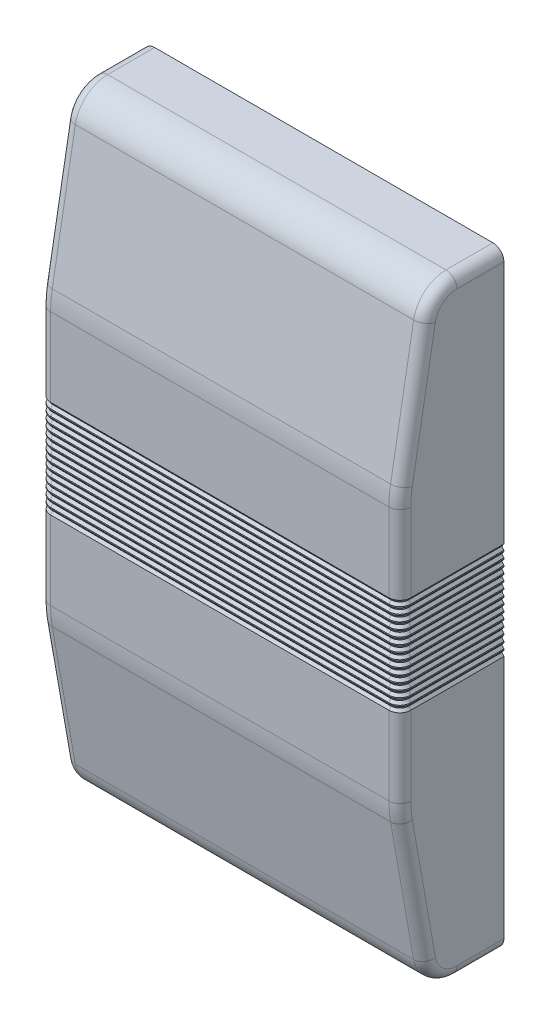
SolidWorks part; units mm, degrees
material "ABS"
ref_plane "Front Plane" through (0, 0, 0) normal (0, 0, 1) x (1, 0, 0)
ref_plane "Top Plane" through (0, 0, 0) normal (0, 1, 0) x (1, 0, 0)
ref_plane "Right Plane" through (0, 0, 0) normal (1, 0, 0) x (0, 0, -1)
sketch "Reference" plane through (0, 0, 0) normal (0, 0, 1) x (1, 0, 0)
  line L1 (0, 0) -> (65.8, 0) construction
  line L2 (0, 0) -> (0, 111.1) construction
  line L3 (0, 111.1) -> (65.8, 111.1) construction
  line L4 (65.8, 0) -> (65.8, 111.1) construction
  dimension "D1" = 65.8
  dimension "D2" = 111.1
sketch "Sketch2" plane through (0, 0, 0) normal (1, 0, 0) x (0, 0, -1)
  line L0 (0, 111.1) -> (-13.6132, 111.1)
  line L1 (0, 0) -> (0, 111.1) construction
  line L2 (0, 0) -> (0, 111.1) construction
  line L3 (-13.6132, 111.1) -> (-19, 80.55)
  line L4 (-19, 80.55) -> (-19, 30.55)
  line L5 (-19, 30.55) -> (-13.6132, 0)
  line L6 (-13.6132, 0) -> (0, 0)
  line L7 (0, 111.1) -> (0, 0)
  point P13 (0, 55.55)
  point P16 (-19, 55.55)
  point P32 (-19, 80.55)
  dimension "D3" = 50
  dimension "D4" = 19
  dimension "D8" = 170
extrude "Extrude side profile" add sketch "Sketch2" along normal up to vertex (65.8 mm away) up to point (65.8, 111.1, 0)
fillet "Cosmetic fillet" radius 20 2 edges at (32.9, 80.55, 19) (32.9, 30.55, 19)
fillet "Cosmetic fillet 2" radius 6 2 edges at (32.9, 0, 13.6132) (32.9, 111.1, 13.6132)
fillet "Cosmetic fillet 3" radius 2 18 edges at (0, 0, 4.2893) (0, 1.4037, 12.4353) (0, 16.8925, 16.5918) (0, 30.5567, 18.9239) (0, 55.55, 19) (0, 80.5433, 18.9239) (0, 94.2075, 16.5918) (0, 109.6963, 12.4353) (65.8, 0, 4.2893) (65.8, 1.4037, 12.4353) (65.8, 16.8925, 16.5918) (65.8, 30.5567, 18.9239) (65.8, 55.55, 19) (65.8, 80.5433, 18.9239) (65.8, 94.2075, 16.5918) (65.8, 109.6963, 12.4353) (0, 111.1, 4.2893) (65.8, 111.1, 4.2893)
shell "Shell1" thickness 3.2
fillet "Fillet internals" radius 1.5 18 edges at (3.2, 107.9, 4.2893) (3.2, 107.2449, 10.3784) (3.2, 93.6519, 13.4404) (3.2, 80.2644, 15.7361) (3.2, 55.55, 15.8) (3.2, 30.8356, 15.7361) (3.2, 17.4481, 13.4404) (3.2, 3.8551, 10.3784) (62.6, 3.2, 4.2893) (62.6, 3.8551, 10.3784) (62.6, 17.4481, 13.4404) (62.6, 30.8356, 15.7361) (62.6, 55.55, 15.8) (62.6, 80.2644, 15.7361) (62.6, 93.6519, 13.4404) (62.6, 107.2449, 10.3784) (3.2, 3.2, 4.2893) (62.6, 107.9, 4.2893)
sketch "Sketch3" plane through (0, 0, 0) normal (0, 0, -1) x (-1, 0, 0)
  line L37 (-63.8, 111.1) -> (-2, 111.1) construction
  line L38 (0, 2) -> (0, 109.1) construction
  line L39 (-63.8, 0) -> (-2, 0) construction
  line L40 (-65.8, 2) -> (-65.8, 109.1) construction
  line L45 (-1.6, 4.7) -> (-1.6, 106.4)
  line L46 (-61.1, 1.6) -> (-4.7, 1.6)
  line L47 (-64.2, 106.4) -> (-64.2, 4.7)
  line L48 (-4.7, 109.5) -> (-61.1, 109.5)
  line L49 (-61.1, 3.2) -> (-4.7, 3.2)
  line L50 (-62.6, 106.4) -> (-62.6, 4.7)
  line L51 (-4.7, 107.9) -> (-61.1, 107.9)
  line L52 (-3.2, 4.7) -> (-3.2, 106.4)
  line L53 (-61.1, 3.2) -> (-4.7, 3.2)
  line L54 (-62.6, 106.4) -> (-62.6, 4.7)
  line L55 (-4.7, 107.9) -> (-61.1, 107.9)
  line L56 (-3.2, 4.7) -> (-3.2, 106.4)
  line L57 (-61.1, 3.2) -> (-61.1, 1.6)
  line L58 (-62.6, 4.7) -> (-64.2, 4.7)
  line L59 (-4.7, 3.2) -> (-4.7, 1.6)
  line L60 (-3.2, 4.7) -> (-1.6, 4.7)
  line L61 (-3.2, 106.4) -> (-1.6, 106.4)
  line L62 (-4.7, 107.9) -> (-4.7, 109.5)
  line L63 (-61.1, 107.9) -> (-61.1, 109.5)
  line L64 (-62.6, 106.4) -> (-64.2, 106.4)
  arc A36 (-62.6, 4.7) -> (-61.1, 3.2) centre (-61.1, 4.7) ccw
  arc A37 (-61.1, 107.9) -> (-62.6, 106.4) centre (-61.1, 106.4) ccw
  arc A38 (-3.2, 106.4) -> (-4.7, 107.9) centre (-4.7, 106.4) ccw
  arc A39 (-4.7, 3.2) -> (-3.2, 4.7) centre (-4.7, 4.7) ccw
  dimension "D1" = 1.6
  dimension "D2" = 0
  dimension "D3" = 1.6
  dimension "D4" = 1.6
  dimension "D5" = 1.6
extrude "Extrude mating boss" add sketch "Sketch3" along normal blind 1.5
other "Tolerance mating boss" face at (32.9, 109.5, -0.75) face at (1.6, 55.55, -0.75) face at (32.9, 1.6, -0.75) face at (64.2, 55.55, -0.75) parameters "D1"=0.2
ref_plane "Mid plane" through (0, 55.55, 0) normal (0, 1, 0) x (1, 0, 0)
sketch "Intersection curve" plane through (0, 55.55, 0) normal (0, 1, 0) x (1, 0, 0)
  line L0 (63.8, -19) -> (2, -19)
  line L1 (63.8, -19) -> (2, -19)
  line L2 (0, -17) -> (0, 0)
  line L3 (0, -17) -> (0, 0)
  line L4 (65.8, -17) -> (65.8, 0)
  line L5 (65.8, -17) -> (65.8, 0)
  arc A0 (0, -17) -> (2, -19) centre (2, -17) ccw
  arc A1 (0, -17) -> (2, -19) centre (2, -17) ccw
  arc A2 (63.8, -19) -> (65.8, -17) centre (63.8, -17) ccw
  arc A3 (63.8, -19) -> (65.8, -17) centre (63.8, -17) ccw
sketch "Cut profile" plane through (0, 0, 0) normal (0, 0, -1) x (-1, 0, 0)
  line L0 (-65.8, 56.05) -> (-65.4499, 55.55)
  line L2 (-65.4499, 55.55) -> (-65.8, 55.05)
  line L4 (-65.8, 56.05) -> (-65.8, 55.05)
  line L5 (-65.8, 2) -> (-65.8, 109.1) construction
  line L6 (-63.8, 55.55) -> (-65.8, 55.55) construction
  point P4 (-65.8, 55.55)
  dimension "D1" = 110
  dimension "D2" = 1
sweep "Cut groove" cut profiles "Cut profile" path "Intersection curve"
pattern_linear "Pattern grooves" count 8 spacing 1.2 along (0, 1, 0) count 8 spacing 1.2 along (0, -1, 0) of "Cut groove"
